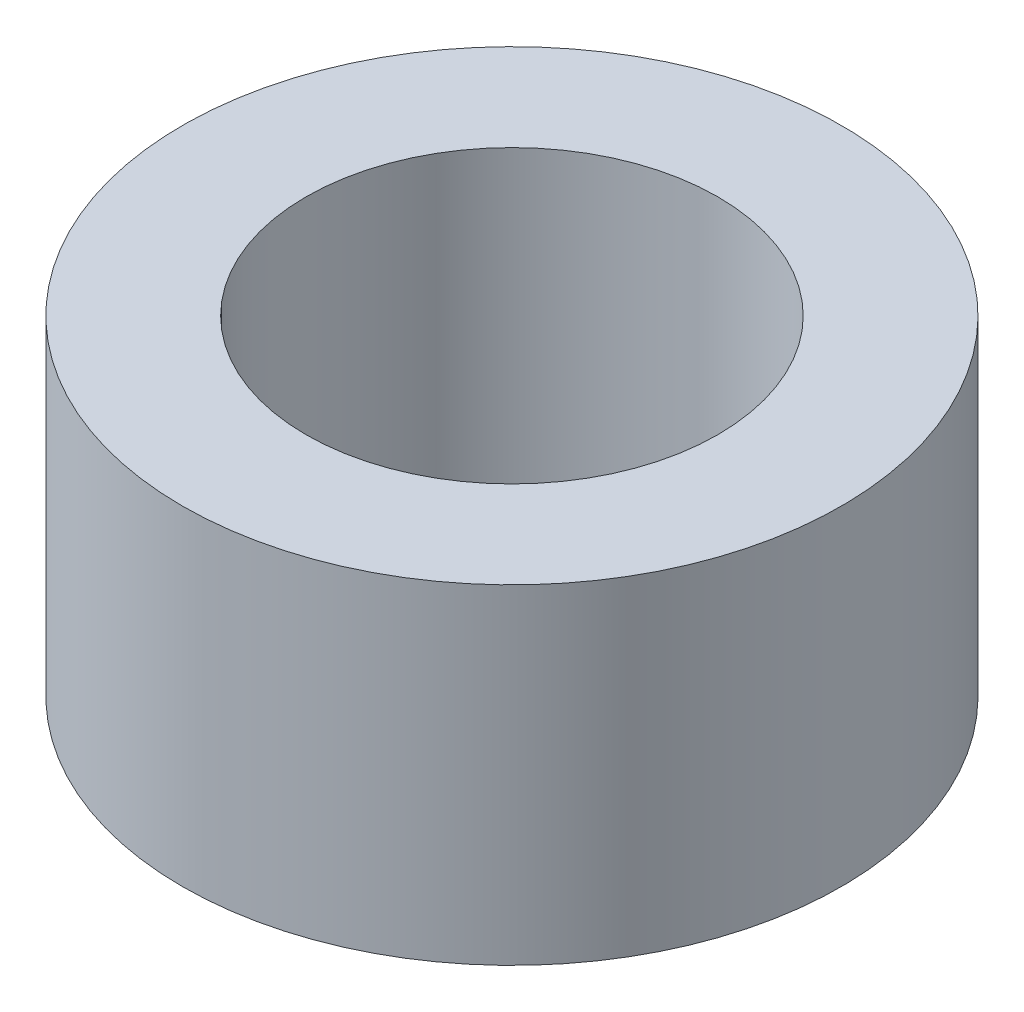
SolidWorks part; units mm, degrees
ref_plane "Front Plane" through (0, 0, 0) normal (0, 0, 1) x (1, 0, 0)
ref_plane "Top Plane" through (0, 0, 0) normal (0, 1, 0) x (1, 0, 0)
ref_plane "Right Plane" through (0, 0, 0) normal (1, 0, 0) x (0, 0, -1)
sketch "Sketch1" plane through (0, 0, 0) normal (0, 1, 0) x (1, 0, 0)
  circle A0 centre (0, 0) radius 20
  circle A1 centre (0, 0) radius 12.5
  dimension "D1" = 25
  dimension "D2" = 40
extrude "Boss-Extrude1" add sketch "Sketch1" along normal mid plane 20
